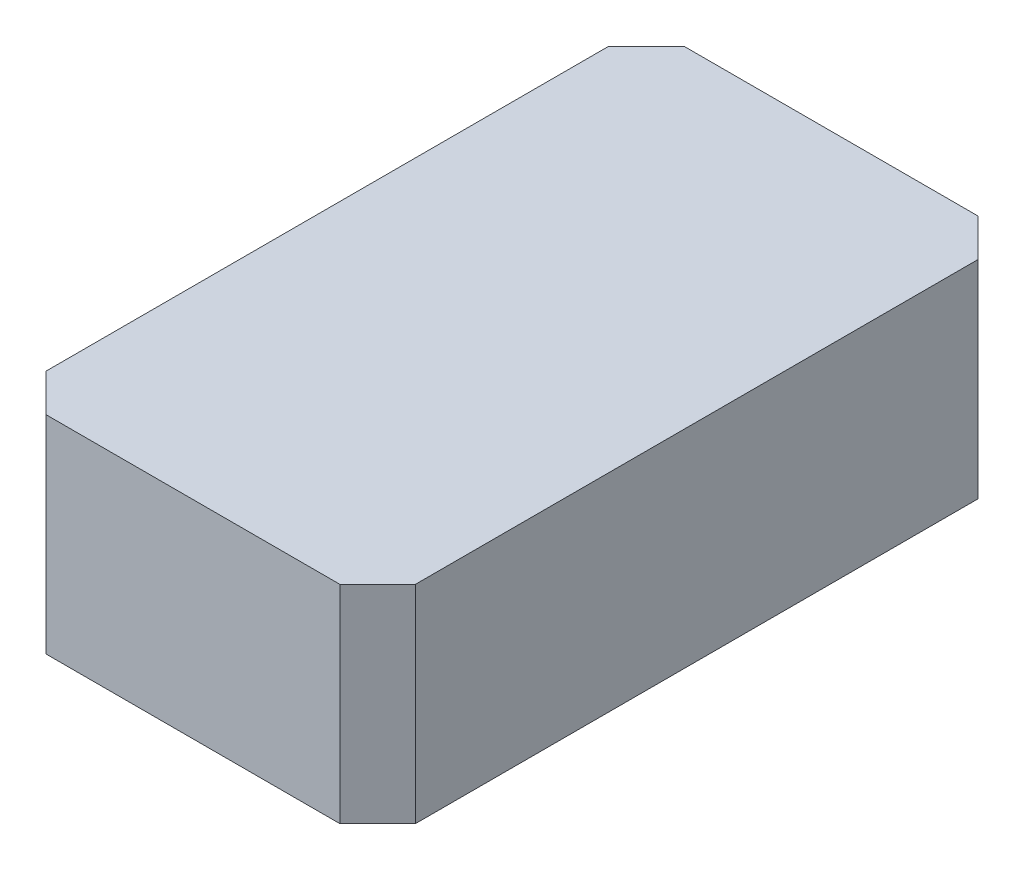
SolidWorks part; units mm, degrees
ref_plane "Front Plane" through (0, 0, 0) normal (0, 0, 1) x (1, 0, 0)
ref_plane "Top Plane" through (0, 0, 0) normal (0, 1, 0) x (1, 0, 0)
ref_plane "Right Plane" through (0, 0, 0) normal (1, 0, 0) x (0, 0, -1)
sketch "Sketch1" plane through (0, 0, 0) normal (0, 1, 0) x (1, 0, 0)
  line L0 (7.8, 14.93) -> (8.8, 14.93)
  line L1 (0, 0) -> (7.8, 0)
  line L2 (0, 0) -> (0, 14.93)
  line L3 (0, 14.93) -> (7.8, 14.93)
  line L4 (7.8, 0) -> (7.8, 14.93)
  line L5 (7.8, 14.93) -> (7.8, 15.93)
  line L6 (7.8, 15.93) -> (8.8, 14.93)
  line L7 (8.8, 14.93) -> (8.8, 0)
  line L8 (8.8, 0) -> (7.8, -1)
  line L9 (7.8, -1) -> (7.8, 0)
  line L10 (7.8, -1) -> (0, -1)
  line L11 (0, -1) -> (-1, 0)
  line L12 (0, 1.2053) -> (0, 0)
  line L13 (-1, 0) -> (0, 0)
  line L14 (-1, 0) -> (-1, 14.93)
  line L15 (-1, 14.93) -> (0, 15.93)
  line L16 (0, 15.93) -> (0, 14.93)
  line L17 (7.8, 15.93) -> (0, 15.93)
extrude "Boss-Extrude1" add sketch "Sketch1" along normal blind 5 contours L5 L17 L16 L3 | L6 L5 L0 | L9 L8 L7 L0 L4 | L13 L11 L10 L9 L1 | L16 L15 L14 L13 L2
sketch "Sketch2" plane through (0, 0, 0) normal (1, 0, 0) x (0, 0, -1)
  line L0 (7.465, 0) -> (7.465, 1)
  line L1 (14.93, 0) -> (0, 0) construction
  line L2 (7.465, 0.5) -> (14.93, 0.5)
  line L3 (14.93, 5) -> (14.93, 0) construction
  line L4 (14.93, 0.5) -> (14.93, 1)
  line L5 (14.93, 1) -> (7.465, 1)
  line L6 (7.465, 1) -> (0, 1)
  line L7 (0, 5) -> (0, 0) construction
  line L8 (0, 1) -> (0, 0.5)
  line L9 (0, 0.5) -> (7.465, 0.5)
  line M9 (14.93, 0) -> (14.93, 5)
  line M11 (0, 5) -> (0, 0)
extrude "Cut-Extrude1" cut sketch "Sketch2" against normal blind 0.5 contours L5 L0 L2 M9 | L9 L0 L6 M11
sketch "Sketch3" plane through (7.8, 0, 0) normal (-1, 0, 0) x (0, 0, 1)
  line L0 (0, 5) -> (0, 0) construction
  line L1 (-14.93, 0) -> (0, 0)
  line L2 (-14.93, 0) -> (-14.93, 1)
  line L3 (-14.93, 1) -> (0, 1)
  line L4 (0, 0) -> (0, 1)
  line L5 (-14.93, 0.5) -> (0, 0.5)
  line M8 (-14.93, 5) -> (-14.93, 0)
extrude "Cut-Extrude2" cut sketch "Sketch3" against normal blind 0.5 contours L5 L4 L3 M8
sketch "Sketch4" plane through (0, 5, 0) normal (0, 1, 0) x (1, 0, 0)
  line L0 (-1, 0) -> (0, -1)
  line L1 (0, -1) -> (7.8, -1)
  line L2 (7.8, -1) -> (8.8, 0)
  line L3 (8.8, 0) -> (8.8, 14.93)
  line L4 (8.8, 14.93) -> (7.8, 15.93)
  line L5 (7.8, 15.93) -> (0, 15.93)
  line L6 (0, 15.93) -> (-1, 14.93)
  line L7 (-1, 14.93) -> (-1, 0)
extrude "Boss-Extrude2" add sketch "Sketch4" along normal blind 0.5
sketch "Sketch5" plane through (0, 5, 0) normal (0, -1, 0) x (1, 0, 0)
  line L0 (3.9, 0) -> (3.9, -1.2081)
  line L2 (0, -14.93) -> (7.8, -14.93) construction
  line L3 (3.9, -14.93) -> (3.9, -13.93)
  line L4 (3.9, -13.93) -> (3.9, -14.4034)
  line L5 (0, 0) -> (7.8, 0) construction
  line L6 (3.9, -1.2081) -> (3.9, -9.5381)
  line L7 (3.9, -9.5381) -> (3.9, -13.93)
  line L8 (3.9, -11.7341) -> (2.9, -11.7341)
  line L9 (3.9, -11.7341) -> (4.9, -11.7341)
  line L10 (4.9, -11.7341) -> (4.9, -13.93)
  line L11 (4.9, -13.93) -> (3.9, -13.93)
  line L12 (2.9, -11.7341) -> (2.9, -13.93)
  line L13 (2.9, -13.93) -> (3.9, -13.93)
  line L14 (3.9, -9.5381) -> (2.9, -9.5381)
  line L15 (2.9, -9.5381) -> (2.9, -11.7341)
  line L16 (4.9, -11.7341) -> (4.9, -9.5381)
  line L17 (4.9, -9.5381) -> (3.9, -9.5381)
extrude "Boss-Extrude3" add sketch "Sketch5" along normal blind 7.5 contours L11 L10 L9 L7 | L12 L13 L7 L8 | L14 L15 L8 L7 | L16 L17 L7 L9
sketch "Sketch6" plane through (0, -2.5, 0) normal (0, -1, 0) x (1, 0, 0)
  line L0 (2.9, -11.7341) -> (4.9, -11.7341)
  line L1 (2.9, -9.5381) -> (2.9, -13.93) construction
  line L2 (4.9, -9.5381) -> (4.9, -13.93) construction
  line L3 (4.9, -11.7341) -> (3.9, -11.7341)
  line L4 (3.9, -11.7341) -> (3.9, -10.7341)
  line L12 (3.9, -10.7341) -> (4.1, -10.7341)
  line L13 (4.1, -10.7341) -> (3.9, -10.7341)
  line L14 (3.9, -10.7341) -> (3.7, -10.7341)
  line L15 (3.7, -10.7341) -> (3.7, -12.7687)
  line L16 (3.7, -12.7687) -> (4.1, -12.7687)
  line L17 (4.1, -12.7687) -> (4.1, -10.7341)
  line L18 (3.9, -11.7341) -> (3.9, -11.2341)
  line L19 (3.9, -11.2341) -> (4.6, -11.2341)
  line L20 (4.6, -11.2341) -> (4.6, -12.2341)
  line L21 (4.6, -12.2341) -> (3.9861, -12.2341)
  line L22 (3.9861, -12.2341) -> (3.2861, -12.2341)
  line L23 (3.2861, -12.2341) -> (3.2861, -11.2341)
  line L24 (3.2861, -11.2341) -> (3.9, -11.2341)
extrude "Boss-Extrude4" add sketch "Sketch6" along normal blind 0.5 contours L4 L19 L17 L12 | L15 L24 L4 L14 | L24 L15 L0 L4 | L19 L4 L0 L17 | L20 L19 L17 L3 | L21 L20 L3 L17 | L22 L21 L17 L0 L15 | L24 L23 L0 L15 | L23 L22 L15 L0 | L21 L22 L15 L16 L17
sketch "Sketch8" plane through (7.8, 0, 0) normal (-1, 0, 0) x (0, 0, 1)
  line L0 (-14.93, 5) -> (-14.93, 1) construction
  line L1 (-14.93, 1.0843) -> (0, 1.0843)
  line L2 (-14.93, 1.0843) -> (-14.93, 1.5843)
  line L3 (-14.93, 1.5843) -> (0, 1.5843)
  line L4 (0, 1.0843) -> (0, 1.5843)
  line L5 (0, 5) -> (0, 1) construction
extrude "Cut-Extrude3" cut sketch "Sketch8" against normal blind 0.5
sketch "Sketch9" plane through (7.8, 0, 0) normal (-1, 0, 0) x (0, 0, 1)
  line L1 (-14.93, 1) -> (0, 1)
  line L2 (-14.93, 1) -> (-14.93, 1.0843)
  line L3 (-14.93, 1.0843) -> (0, 1.0843)
  line L4 (0, 1) -> (0, 1.0843)
extrude "Cut-Extrude4" cut sketch "Sketch9" against normal blind 0.5
ref_plane "Plane1" through (0, 1, 0) normal (0, 0, 1) x (1, 0, 0)
sketch "Sketch12" plane through (0, 0, 0) normal (1, 0, 0) x (0, 0, -1)
  line L0 (14.93, 5) -> (14.93, 1) construction
  line L1 (0, 1) -> (14.93, 1)
  line L2 (0, 1) -> (0, 2.2)
  line L3 (0, 2.2) -> (14.93, 2.2)
  line L4 (14.93, 1) -> (14.93, 2.2)
extrude "Cut-Extrude5" cut sketch "Sketch12" against normal blind 0.5
